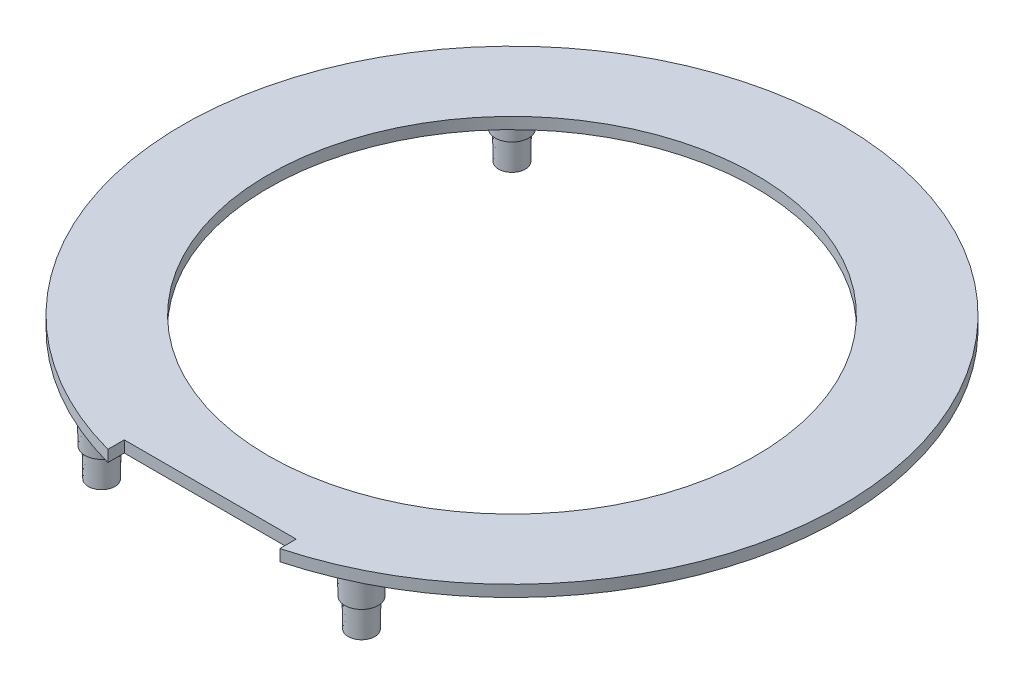
SolidWorks part; units mm, degrees
ref_plane "Front Plane" through (0, 0, 0) normal (0, 0, 1) x (1, 0, 0)
ref_plane "Top Plane" through (0, 0, 0) normal (0, 1, 0) x (1, 0, 0)
ref_plane "Right Plane" through (0, 0, 0) normal (1, 0, 0) x (0, 0, -1)
sketch "Sketch1" plane through (0, 0, 0) normal (0, 1, 0) x (1, 0, 0)
  circle A0 centre (0, 1.5306) radius 11.5
  circle A1 centre (0, 1.5306) radius 8.5
  dimension "D1" = 23
  dimension "D2" = 17
  dimension "D3" = 1.5306
extrude "Boss-Extrude1" add sketch "Sketch1" along normal blind 0.4
sketch "Sketch2" plane through (0, 0, 0) normal (0, 1, 0) x (1, 0, 0)
  line L0 (0, 1.5306) -> (-4.6159, -8.1752) construction
  line L1 (0, 1.5306) -> (0, -4.7232) construction
  line L2 (0, 1.5306) -> (4.4541, -8.1752) construction
  circle A0 centre (-4.6159, -8.1752) radius 0.6
  circle A1 centre (-7.0459, 8.5748) radius 0.6
  circle A2 centre (7.7441, 8.5748) radius 0.6
  circle A3 centre (4.4541, -8.1752) radius 0.6
  point P6 (7.0459, 8.5748)
  point P11 (7.7441, 8.5748)
  point P12 (4.4541, -8.1752)
  point P13 (0, 0)
  point P16 (0, 0)
  dimension "D2" = 1.2
extrude "Boss-Extrude2" add sketch "Sketch2" against normal blind 1
sketch "Sketch3" plane through (0, -1, 0) normal (0, -1, 0) x (1, 0, 0)
  line L0 (0, 0) -> (0, -5.4861) construction
  circle A0 centre (-4.6159, 8.1752) radius 0.5
  circle A1 centre (-7.0459, -8.5748) radius 0.5
  circle A2 centre (7.7441, -8.5748) radius 0.5
  circle A3 centre (4.4541, 8.1752) radius 0.5
  point P12 (-8.1253, -7.6435)
  point P14 (7.0459, -8.5748)
  point P15 (7.7441, -8.5748)
  point P17 (4.6159, 8.1752)
  point P18 (4.4541, 8.1752)
  point P20 (-4.6159, 8.1752)
  point P22 (4.4541, 8.1752)
  dimension "D1" = 1
extrude "Boss-Extrude3" add sketch "Sketch3" along normal blind 1
sketch "Sketch4" plane through (0, 0.4, 0) normal (0, 1, 0) x (1, 0, 0)
  line L0 (-0.75, 13.0062) -> (-0.75, 11.001) construction
  line L1 (0, -0.22) -> (0, 0.22) construction
  line L2 (0.75, 13.0062) -> (0.75, 11.001) construction
  circle A0 centre (0, 1.5306) radius 9.5 construction
  circle A1 centre (0, 1.5306) radius 11.5 construction
  circle A2 centre (0, 1.5306) radius 11.5 construction
  dimension "D1" = 19
  dimension "D3" = 1.5
sketch "Sketch5" plane through (0, 0.4, 0) normal (0, 1, 0) x (1, 0, 0)
  line L0 (-0.75, 13.0062) -> (-0.75, 11.001) construction
  line L1 (-0.75, 13.0062) -> (-0.75, 11.001)
  line L2 (0.75, 13.0062) -> (0.75, 11.001) construction
  line L3 (0.75, 13.0062) -> (0.75, 11.001)
  circle A0 centre (0, 1.5306) radius 11.5 construction
  arc A1 (0.75, 13.0062) -> (-0.75, 13.0062) centre (0, 1.5306) ccw
  circle A2 centre (0, 1.5306) radius 9.5 construction
  arc A3 (0.75, 11.001) -> (-0.75, 11.001) centre (0, 1.5306) ccw
sketch "Sketch6" plane through (0, 0.4, 0) normal (0, 1, 0) x (1, 0, 0)
  line L0 (0, 0) -> (0, -9) construction
  line L1 (3, -9) -> (-3, -9)
  line L2 (-3, -9) -> (-3, -9.5712)
  line L3 (3, -9) -> (3, -9.5712)
  circle A0 centre (0, 1.5306) radius 11.5 construction
  arc A1 (-3, -9.5712) -> (3, -9.5712) centre (0, 1.5306) ccw
  point P6 (0, -9)
  dimension "D1" = 9
  dimension "D2" = 6
  dimension "D3" = 90
extrude "Cut-Extrude1" cut sketch "Sketch6" against normal up to surface (0.4 mm away) up to face at (4.4541, 0, 7.5752)
draft "Draft2" type of draft neutral plane draft angle 1 neutral plane "Top Plane" faces to draft 8 face at (7.7441, -2, -8.0748) face at (7.7441, -1, -9.1748) face at (4.4541, -1, 7.5752) face at (4.4541, -2, 8.6752) face at (-4.6159, -2, 7.6752) face at (-4.6159, -1, 8.7752) face at (-7.0459, -1, -7.9748) face at (-7.0459, -2, -9.0748) neutral plane through (0, 0, 0) neutral plane normal (0, 1, 0) reverse direction yes parameters "D1"=1
